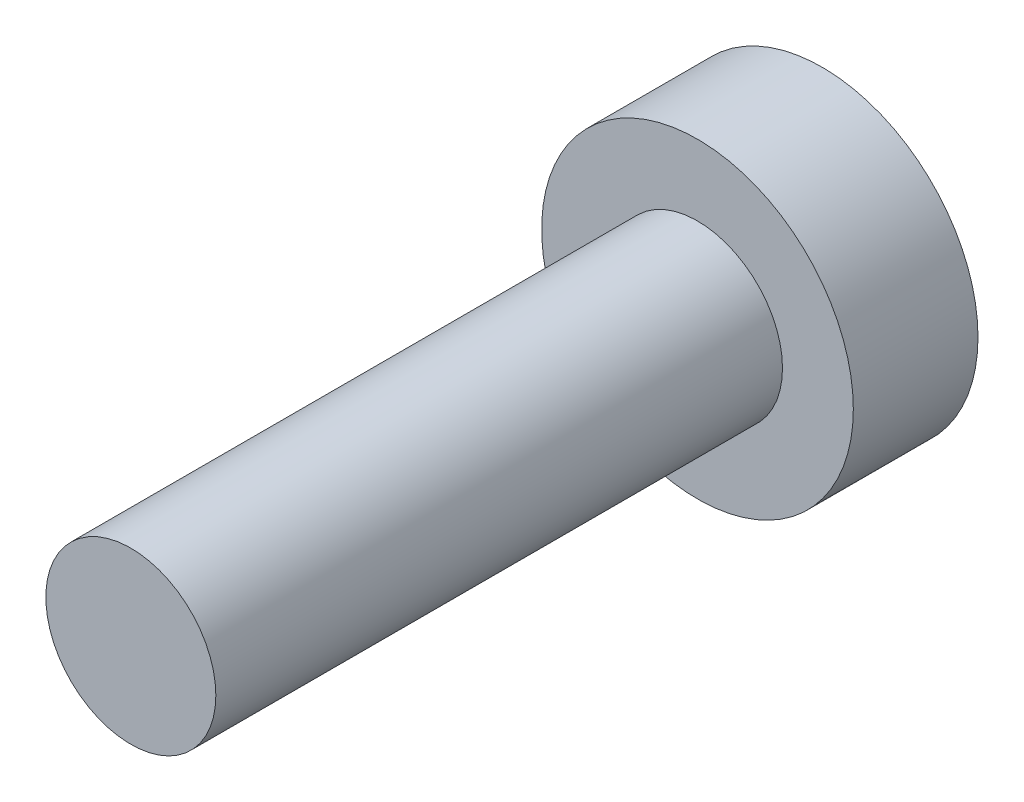
SolidWorks part; units mm, degrees
material "AISI 304"
ref_plane "前视基准面" through (0, 0, 0) normal (0, 0, 1) x (1, 0, 0)
ref_plane "上视基准面" through (0, 0, 0) normal (0, 1, 0) x (1, 0, 0)
ref_plane "右视基准面" through (0, 0, 0) normal (1, 0, 0) x (0, 0, -1)
sketch "草图1" plane through (0, 0, 0) normal (0, 0, 1) x (1, 0, 0)
  circle A0 centre (0, 0) radius 2.75
  dimension "D1" = 5.5
extrude "凸台-拉伸1" add sketch "草图1" along normal blind 2.2
sketch "草图2" plane through (0, 0, 2.2) normal (0, 0, 1) x (1, 0, 0)
  circle A0 centre (0, 0) radius 1.5
  dimension "D1" = 3
extrude "凸台-拉伸2" add sketch "草图2" along normal blind 10
